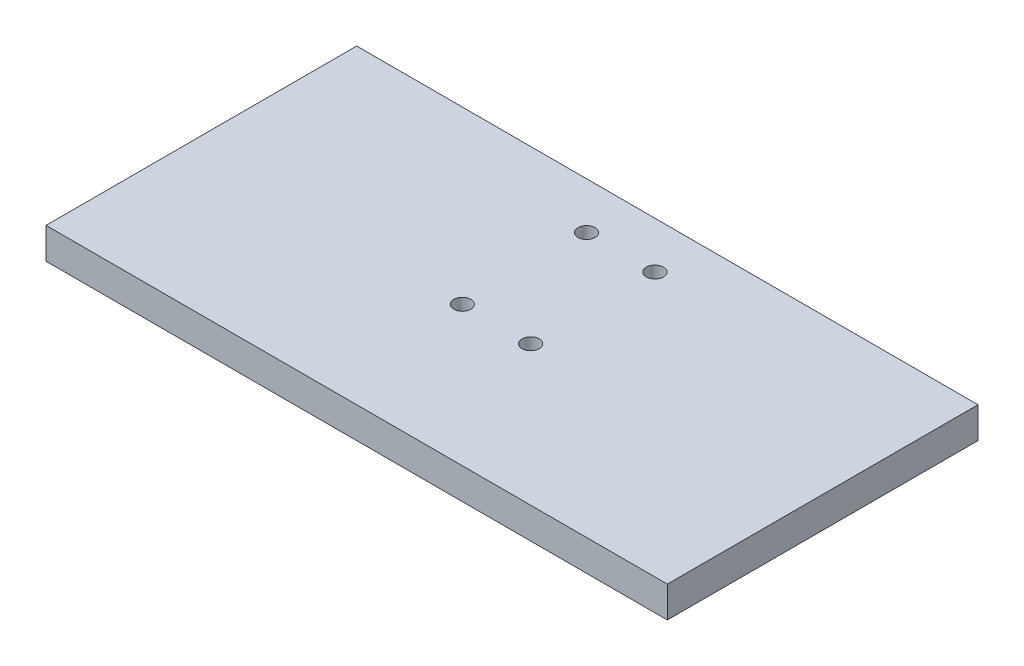
SolidWorks part; units mm, degrees
ref_plane "정면" through (0, 0, 0) normal (0, 0, 1) x (1, 0, 0)
ref_plane "윗면" through (0, 0, 0) normal (0, 1, 0) x (1, 0, 0)
ref_plane "우측면" through (0, 0, 0) normal (1, 0, 0) x (0, 0, -1)
sketch "스케치1" plane through (0, 0, 0) normal (0, 1, 0) x (1, 0, 0)
  line L1 (0, 0) -> (200, 0)
  line L2 (0, 0) -> (0, 100)
  line L3 (0, 100) -> (200, 100)
  line L4 (200, 0) -> (200, 100)
  dimension "D1" = 200
  dimension "D2" = 100
extrude "보스-돌출1" add sketch "스케치1" along normal blind 10
sketch "스케치3" plane through (0, 0, 0) normal (0, -1, 0) x (1, 0, 0)
  line L0 (100, -100) -> (100, 17.1584) construction
  line L1 (200, -100) -> (0, -100) construction
  point P4 (111, -45)
  point P5 (111, -85)
  point P6 (89, -85)
  point P7 (89, -45)
  dimension "D1" = 40
  dimension "D2" = 22
  dimension "D3" = 15
hole_wizard "M5 치즈머리 홈붙이 머리용 카운터보어2" positions "3D스케치2" profile "스케치5" counterbore size "M5" standard "KS" end condition through all
sketch3d "3D스케치2"
  point P0 (89, 0, -45)
  point P3 (111, 0, -45)
  point P6 (111, 0, -85)
  point P9 (89, 0, -85)
sketch "스케치5" plane through (89, 0, -45) normal (1, 0, 0) x (0, 0, -1)
  line L0 (0, 0) -> (0, 10)
  line L1 (0, 10) -> (2.75, 10)
  line L3 (2.75, 10) -> (2.75, 3.3)
  line L4 (2.75, 3.3) -> (4.75, 3.3)
  line L5 (4.75, 3.3) -> (4.75, 0)
  line L7 (4.75, 0) -> (0, 0)
  line L11 (0, -6.35) -> (0, 107.95) construction
  dimension "관통 구멍 지름" = 5.5
  dimension "관통 구멍 깊이" = 10
  dimension "카운터보어 지름" = 9.5
  dimension "카운터보어 깊이" = 3.3
